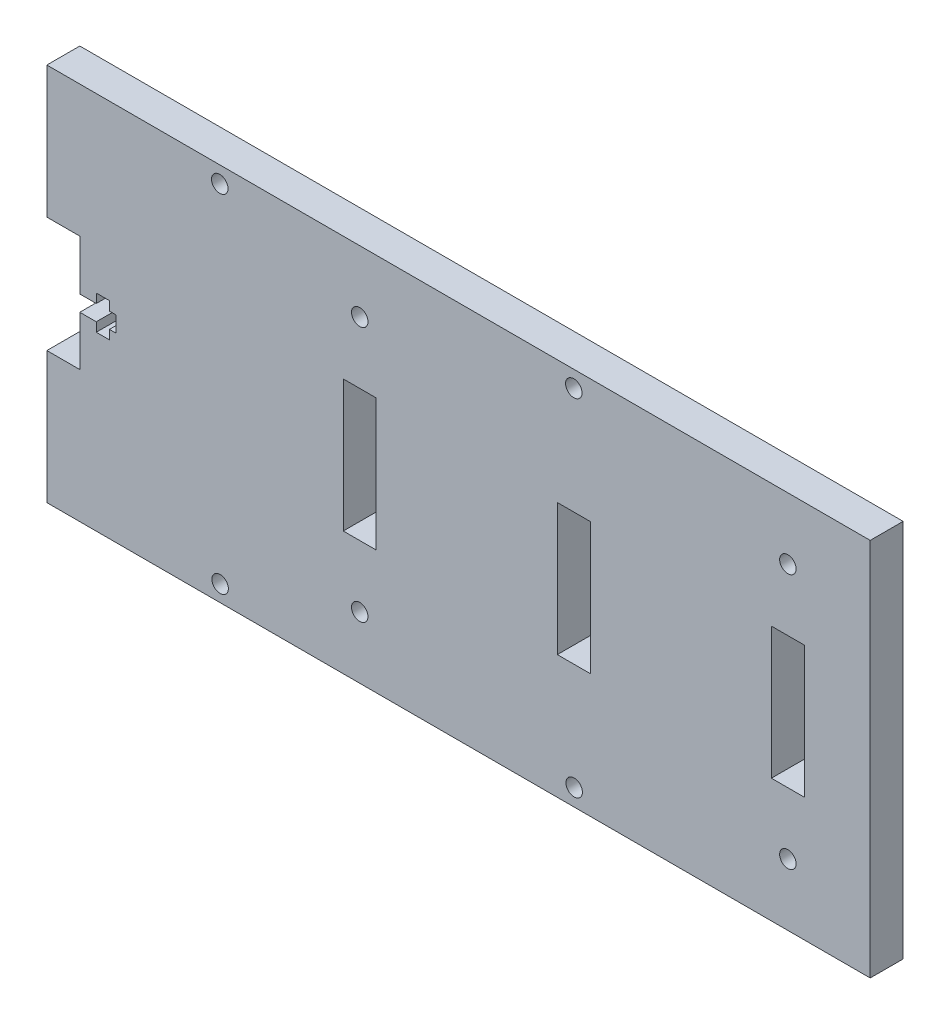
SolidWorks part; units mm, degrees
material "6061 Alloy"
ref_plane "Front Plane" through (0, 0, 0) normal (0, 0, 1) x (1, 0, 0)
ref_plane "Top Plane" through (0, 0, 0) normal (0, 1, 0) x (1, 0, 0)
ref_plane "Right Plane" through (0, 0, 0) normal (1, 0, 0) x (0, 0, -1)
sketch "Sketch1" plane through (0, 0, 0) normal (0, 0, 1) x (1, 0, 0)
  line L0 (-80.7065, -31.5637) -> (-80.7065, -21.9971)
  line L1 (-80.7065, 16.1121) -> (71.6935, 16.1121)
  line L2 (-80.7065, -56.9637) -> (71.6935, -56.9637)
  line L3 (71.6935, -56.9637) -> (71.6935, 16.1121)
  line L4 (-80.7065, 16.1121) -> (-87.0565, 16.1121)
  line L5 (-87.0565, 16.1121) -> (-87.0565, -9.2879)
  line L6 (-87.0565, -9.2879) -> (-80.7065, -9.2879)
  line L7 (-80.7065, -31.5637) -> (-87.0565, -31.5637)
  line L8 (-87.0565, -31.5637) -> (-87.0565, -56.9637)
  line L9 (-87.0565, -56.9637) -> (-80.7065, -56.9637)
  line L10 (-73.7215, -18.9492) -> (-74.9915, -18.9492)
  line L11 (-74.9915, -18.9492) -> (-74.9915, -17.1966)
  line L12 (-74.9915, -17.1966) -> (-77.5315, -17.1966)
  line L13 (-77.5315, -17.1966) -> (-77.5315, -18.9492)
  line L14 (-77.5315, -18.9492) -> (-80.7065, -18.9492)
  line L15 (-73.7215, -21.9971) -> (-74.9915, -21.9971)
  line L16 (-74.9915, -21.9971) -> (-74.9915, -23.7497)
  line L17 (-74.9915, -23.7497) -> (-77.5315, -23.7497)
  line L18 (-77.5315, -23.7497) -> (-77.5315, -21.9971)
  line L19 (-77.5315, -21.9971) -> (-80.7065, -21.9971)
  line L20 (-80.7065, -18.9492) -> (-80.7065, -9.2879)
  line L21 (-29.9065, -33.1258) -> (-23.5565, -33.1258)
  line L22 (-29.9065, -33.1258) -> (-29.9065, -7.7258)
  line L23 (-29.9065, -7.7258) -> (-23.5565, -7.7258)
  line L24 (-23.5565, -7.7258) -> (-23.5565, -33.1258)
  line L25 (52.6435, -33.1258) -> (58.9935, -33.1258)
  line L26 (52.6435, -33.1258) -> (52.6435, -7.7258)
  line L27 (52.6435, -7.7258) -> (58.9935, -7.7258)
  line L28 (58.9935, -7.7258) -> (58.9935, -33.1258)
  line L29 (11.3685, -33.1258) -> (17.7185, -33.1258)
  line L30 (11.3685, -33.1258) -> (11.3685, -7.7258)
  line L31 (11.3685, -7.7258) -> (17.7185, -7.7258)
  line L32 (17.7185, -7.7258) -> (17.7185, -33.1258)
  line L33 (-73.7215, -18.9492) -> (-73.7215, -21.9971)
  circle A0 centre (-26.7315, 4.1932) radius 1.5875
  circle A1 centre (-26.7315, -45.0447) radius 1.5875
  circle A2 centre (55.8185, 4.1932) radius 1.5875
  circle A3 centre (55.8185, -45.0447) radius 1.5875
  circle A4 centre (-53.719, 12.9371) radius 1.5875
  circle A5 centre (14.5435, 12.9371) radius 1.5875
  circle A6 centre (-53.6468, -53.8401) radius 1.5875
  circle A7 centre (14.6155, -53.6925) radius 1.5875
extrude "Boss-Extrude1" add sketch "Sketch1" along normal blind 6.35
